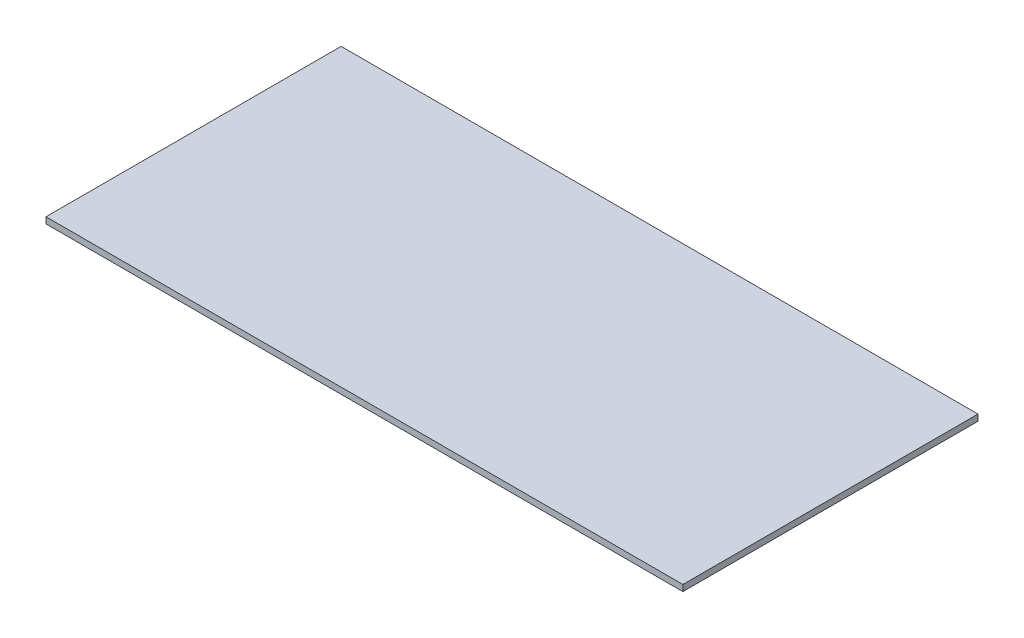
SolidWorks part; units mm, degrees
ref_plane "Front Plane" through (0, 0, 0) normal (0, 0, 1) x (1, 0, 0)
ref_plane "Top Plane" through (0, 0, 0) normal (0, 1, 0) x (1, 0, 0)
ref_plane "Right Plane" through (0, 0, 0) normal (1, 0, 0) x (0, 0, -1)
sketch "Sketch1" plane through (0, 0, 0) normal (0, 1, 0) x (1, 0, 0)
  line L1 (-205, 95) -> (205, 95)
  line L2 (-205, 95) -> (-205, -95)
  line L3 (-205, -95) -> (205, -95)
  line L4 (205, 95) -> (205, -95)
  line L5 (-205, 95) -> (205, -95) construction
  line L6 (-205, -95) -> (205, 95) construction
  point P0 (0, 0)
  dimension "D1" = 410
  dimension "D2" = 190
extrude "Boss-Extrude1" add sketch "Sketch1" along normal blind 4
